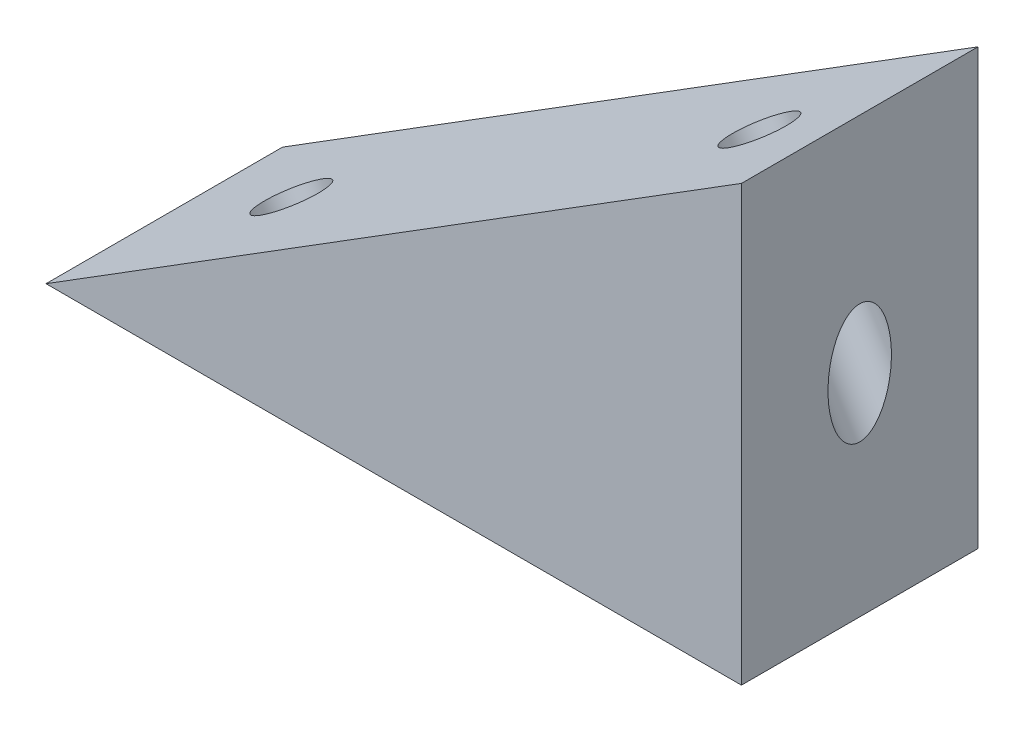
SolidWorks part; units mm, degrees
ref_plane "Front Plane" through (0, 0, 0) normal (0, 0, 1) x (1, 0, 0)
ref_plane "Top Plane" through (0, 0, 0) normal (0, 1, 0) x (1, 0, 0)
ref_plane "Right Plane" through (0, 0, 0) normal (1, 0, 0) x (0, 0, -1)
sketch "Sketch2" plane through (0, 0, 0) normal (0, 0, 1) x (1, 0, 0)
  line L0 (0, 0) -> (0, 34.9927)
  line L1 (0, 34.9927) -> (-56, 0)
  line L2 (-56, 0) -> (0, 0)
  dimension "D1" = 56
  dimension "D2" = 32
extrude "Boss-Extrude1" add sketch "Sketch2" along normal blind 19.05
sketch "Sketch3" plane through (-15.7256, 25.1662, 0) normal (-0.5299, 0.848, 0) x (0.848, 0.5299, 0)
  line L0 (18.5433, -9.525) -> (-47.4907, -9.525) construction
  line L1 (18.5433, -19.05) -> (18.5433, 0) construction
  line L2 (-47.4907, -19.05) -> (-47.4907, 0) construction
  line L3 (-35.4317, 0) -> (-35.4317, -19.05) construction
  line L4 (18.5433, 0) -> (-47.4907, 0) construction
  line L5 (18.5433, -19.05) -> (-47.4907, -19.05) construction
  line L7 (9.0183, 0) -> (9.0183, -19.05) construction
  dimension "D1" = 44.45
  dimension "D2" = 9.525
hole_wizard "#7 (0.201) Diameter Hole1" positions "Sketch4" profile "Sketch5" hole size "#7" standard "ANSI Inch"
sketch "Sketch4" plane through (-15.7256, 25.1662, 0) normal (-0.5299, 0.848, 0) x (0.848, 0.5299, 0)
  line L0 (-35.4317, 0) -> (-35.4317, -19.05) construction
  line L1 (9.0183, 0) -> (9.0183, -19.05) construction
  point P0 (-35.4317, -9.525)
  point P4 (9.0183, -9.525)
sketch "Sketch5" plane through (-45.7734, 6.3903, 9.525) normal (0, 0, 1) x (-0.848, -0.5299, 0)
  line L0 (0, 0) -> (0, 25.4)
  line L1 (0, 25.4) -> (2.5527, 25.4)
  line L2 (2.5527, 25.4) -> (2.5527, 0)
  line L5 (2.5527, 0) -> (0, 0)
  line L10 (0, 25.4) -> (-2.5527, 25.4) construction
  line L11 (0, -6.35) -> (0, 107.95) construction
  dimension "Hole Dia." = 5.1054
  dimension "Hole Depth" = 25.4
  dimension "Drill Angle" = 180
